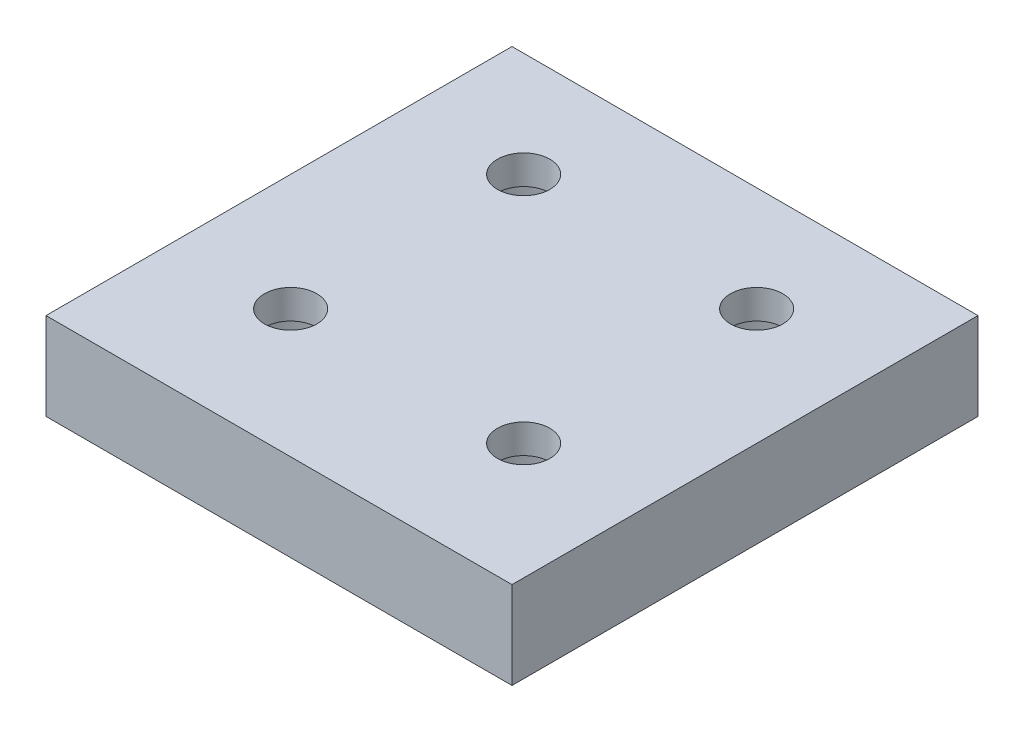
SolidWorks part; units mm, degrees
ref_plane "Alzado" through (0, 0, 0) normal (0, 0, 1) x (1, 0, 0)
ref_plane "Planta" through (0, 0, 0) normal (0, 1, 0) x (1, 0, 0)
ref_plane "Vista lateral" through (0, 0, 0) normal (1, 0, 0) x (0, 0, -1)
sketch "Croquis1" plane through (0, 0, 0) normal (0, 1, 0) x (1, 0, 0)
  line L1 (20, 20) -> (-20, 20)
  line L2 (20, 20) -> (20, -20)
  line L3 (20, -20) -> (-20, -20)
  line L4 (-20, 20) -> (-20, -20)
  line L5 (20, 20) -> (-20, -20) construction
  line L6 (20, -20) -> (-20, 20) construction
  circle A0 centre (-10, 11) radius 2.25
  circle A1 centre (10, 11) radius 2.25
  circle A2 centre (10, -9) radius 2.25
  circle A3 centre (-10, -9) radius 2.25
  point P0 (0, 0)
  point P14 (0, 0)
  point P15 (0, 0)
  dimension "D11" = 4.5
  dimension "D1" = 40
  dimension "D2" = 40
  dimension "D3" = 10
  dimension "D4" = 9
  dimension "D5" = 10
  dimension "D6" = 11
  dimension "D7" = 10
  dimension "D9" = 10
extrude "Saliente-Extruir1" add sketch "Croquis1" along normal blind 7.5 contours L1 L4 L3 L2 A3 A2 A1 A0
sketch "Croquis2" plane through (0, 0, 0) normal (0, -1, 0) x (1, 0, 0)
  circle A2 centre (-10, 9) radius 6.25
  circle A3 centre (-10, 9) radius 6.25
  circle A5 centre (10, 9) radius 6.25
  circle A6 centre (10, 9) radius 6.25
  circle A8 centre (-10, -11) radius 6.25
  circle A9 centre (-10, -11) radius 6.25
  circle A11 centre (10, -11) radius 6.25
  circle A12 centre (10, -11) radius 6.25
  dimension "D1" = 4
  dimension "D2" = 4
  dimension "D3" = 4
  dimension "D4" = 4
extrude "Cortar-Extruir1" cut sketch "Croquis2" against normal blind 5
shell "Vaciado1" thickness 1
fillet "Redondeo1" radius 4 4 edges at (19, 3.25, -19) (-19, 3.25, -19) (19, 3.25, 19) (-19, 3.25, 19)
